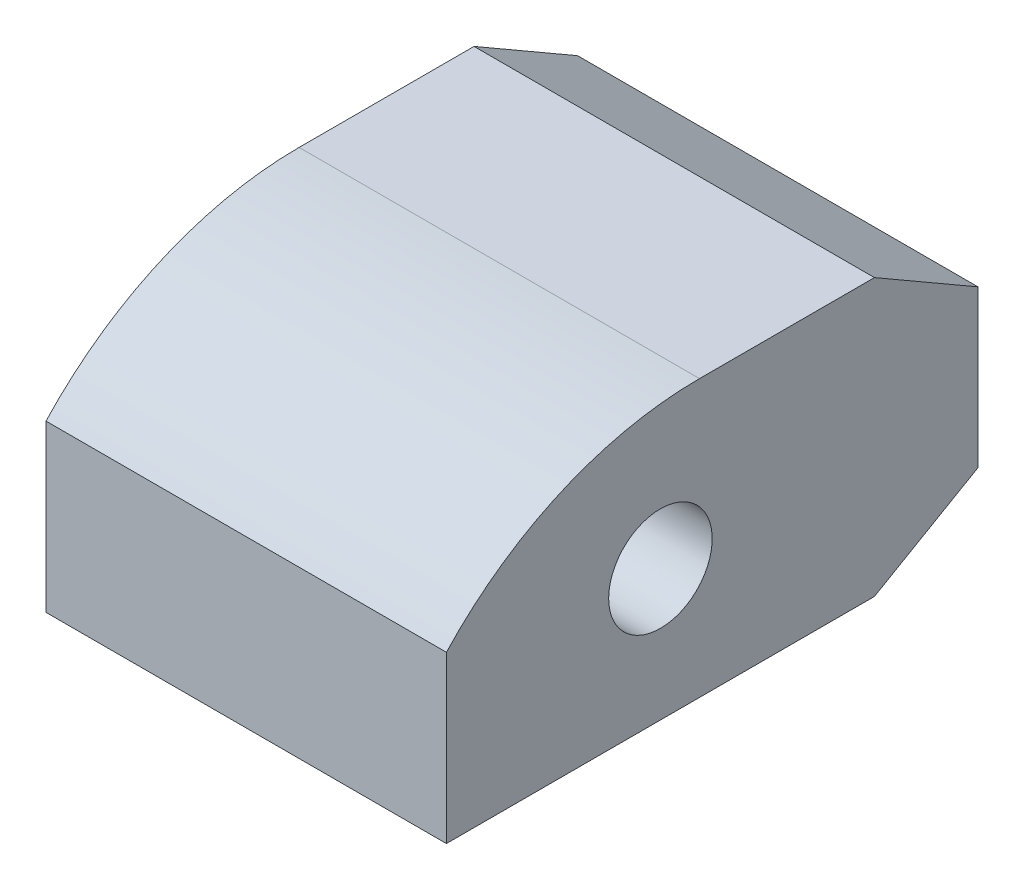
SolidWorks part; units mm, degrees
ref_plane "Front Plane" through (0, 0, 0) normal (0, 0, 1) x (1, 0, 0)
ref_plane "Top Plane" through (0, 0, 0) normal (0, 1, 0) x (1, 0, 0)
ref_plane "Right Plane" through (0, 0, 0) normal (1, 0, 0) x (0, 0, -1)
sketch "Sketch1" plane through (0, 0, 0) normal (1, 0, 0) x (0, 0, -1)
  line L0 (0, 0) -> (0, 22637.3905) construction
  line L1 (1.3894, 0) -> (-22636.0011, 0) construction
  line L2 (-31, 5) -> (-31, -19)
  line L3 (-31, -19) -> (31, -19)
  line L4 (31, -19) -> (46, -10.3397)
  line L5 (46, -10.3397) -> (46, 12.3397)
  line L6 (46, 12.3397) -> (31, 21)
  line L7 (31, 21) -> (5.6606, 21)
  arc A0 (5.6606, 21) -> (-31, 5) centre (5.6606, -29) ccw
  circle A1 centre (0, 0) radius 7.5
  dimension "D7" = 15
  dimension "D11" = 50
  dimension "D2" = 40
  dimension "D3" = 30
  dimension "D4" = 30
  dimension "D5" = 15
  dimension "D6" = 15
  dimension "D8" = 31
  dimension "D9" = 19
  dimension "D10" = 24
  dimension "D12" = 62
extrude "Boss-Extrude1" add sketch "Sketch1" along normal mid plane 58
equation "\"A\"= 58"
equation "\"B\"= 40"
equation "\"C\"= 62"
equation "\"D2@Sketch1\"=\"B\""
equation "\"D1@Boss-Extrude1\"=\"A\""
equation "\"D12@Sketch1\"=\"C\""
